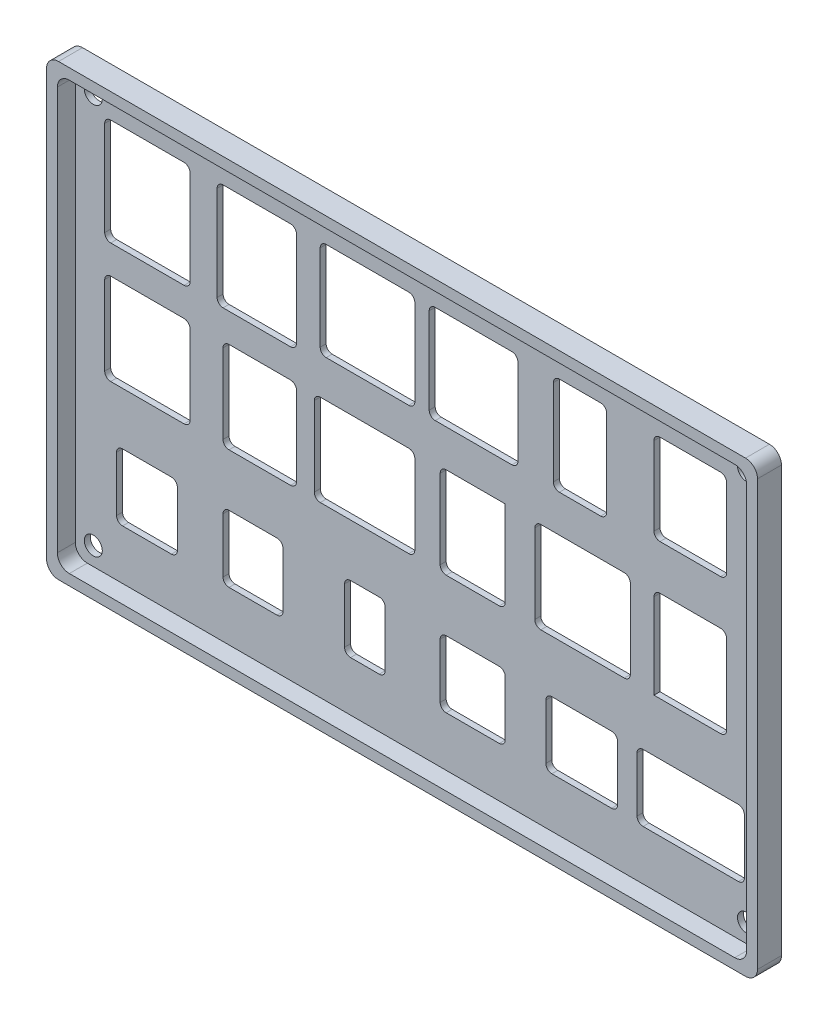
SolidWorks part; units mm, degrees
ref_plane "Front Plane" through (0, 0, 0) normal (0, 0, 1) x (1, 0, 0)
ref_plane "Top Plane" through (0, 0, 0) normal (0, 1, 0) x (1, 0, 0)
ref_plane "Right Plane" through (0, 0, 0) normal (1, 0, 0) x (0, 0, -1)
sketch "Sketch1" plane through (0, 0, 0) normal (0, 0, 1) x (1, 0, 0)
  line L1 (-44.9273, 28.8963) -> (70.105, 28.8963)
  line L2 (-44.9273, 28.8963) -> (-44.9273, -42.4043)
  line L3 (-44.9273, -42.4043) -> (70.105, -42.4043)
  line L4 (70.105, 28.8963) -> (70.105, -42.4043)
  line L5 (-40.0243, 23.5886) -> (-25.7822, 23.5886)
  line L6 (-40.0243, 23.5886) -> (-40.0243, 5.8213)
  line L7 (-40.0243, 5.8213) -> (-25.7822, 5.8213)
  line L8 (-25.7822, 23.5886) -> (-25.7822, 5.8213)
  line L9 (-21.2699, 23.5886) -> (-8.0149, 23.5886)
  line L10 (-21.2699, 23.5886) -> (-21.2699, 5.8213)
  line L11 (-21.2699, 5.8213) -> (-8.0149, 5.8213)
  line L12 (-8.0149, 23.5886) -> (-8.0149, 5.8213)
  line L13 (-4.0666, 23.5886) -> (11.7266, 23.5886)
  line L14 (-4.0666, 23.5886) -> (-4.0666, 7.2314)
  line L15 (-4.0666, 7.2314) -> (11.7266, 7.2314)
  line L16 (11.7266, 23.5886) -> (11.7266, 7.2314)
  line L17 (14.1238, 23.5886) -> (28.9299, 23.5886)
  line L18 (14.1238, 23.5886) -> (14.1238, 7.2314)
  line L19 (14.1238, 7.2314) -> (28.9299, 7.2314)
  line L20 (28.9299, 23.5886) -> (28.9299, 7.2314)
  line L21 (34.8524, 23.5886) -> (43.736, 23.5886)
  line L22 (34.8524, 23.5886) -> (34.8524, 7.2314)
  line L23 (34.8524, 7.2314) -> (43.736, 7.2314)
  line L24 (43.736, 23.5886) -> (43.736, 7.2314)
  line L25 (51.6326, 23.5886) -> (63.7595, 23.5886)
  line L26 (51.6326, 23.5886) -> (51.6326, 8.5005)
  line L27 (51.6326, 8.5005) -> (63.7595, 8.5005)
  line L28 (63.7595, 23.5886) -> (63.7595, 8.5005)
  line L29 (-40.0243, 1.0269) -> (-25.7822, 1.0269)
  line L30 (-40.0243, 1.0269) -> (-40.0243, -14.2022)
  line L31 (-40.0243, -14.2022) -> (-25.7822, -14.2022)
  line L32 (-25.7822, 1.0269) -> (-25.7822, -14.2022)
  line L33 (-20.2828, 1.0269) -> (-8.0149, 1.0269)
  line L34 (-20.2828, 1.0269) -> (-20.2828, -14.2022)
  line L35 (-20.2828, -14.2022) -> (-8.0149, -14.2022)
  line L36 (-8.0149, 1.0269) -> (-8.0149, -14.2022)
  line L37 (-5.0536, 1.0269) -> (11.7266, 1.0269)
  line L38 (-5.0536, 1.0269) -> (-5.0536, -14.2022)
  line L39 (-5.0536, -14.2022) -> (11.7266, -14.2022)
  line L40 (11.7266, 1.0269) -> (11.7266, -14.2022)
  line L41 (15.9569, 1.0269) -> (26.8148, 1.0269)
  line L42 (15.9569, 1.0269) -> (15.9569, -14.2022)
  line L43 (15.9569, -14.2022) -> (26.8148, -14.2022)
  line L44 (26.8148, 1.0269) -> (26.8148, -14.2022)
  line L45 (31.7501, 1.0269) -> (47.6843, 1.0269)
  line L46 (31.7501, 1.0269) -> (31.7501, -14.2022)
  line L47 (31.7501, -14.2022) -> (47.6843, -14.2022)
  line L48 (47.6843, 1.0269) -> (47.6843, -14.2022)
  line L49 (51.6326, 1.0269) -> (63.7595, 1.0269)
  line L50 (51.6326, 1.0269) -> (51.6326, -14.2022)
  line L51 (51.6326, -14.2022) -> (63.7595, -14.2022)
  line L52 (63.7595, 1.0269) -> (63.7595, -14.2022)
  line L53 (-38.0501, -22.9449) -> (-27.8974, -22.9449)
  line L54 (-38.0501, -22.9449) -> (-38.0501, -34.0847)
  line L55 (-38.0501, -34.0847) -> (-27.8974, -34.0847)
  line L56 (-27.8974, -22.9449) -> (-27.8974, -34.0847)
  line L57 (-20.2828, -22.9449) -> (-10.271, -22.9449)
  line L58 (-20.2828, -22.9449) -> (-20.2828, -34.0847)
  line L59 (-20.2828, -34.0847) -> (-10.271, -34.0847)
  line L60 (-10.271, -22.9449) -> (-10.271, -34.0847)
  line L61 (0, -22.9449) -> (6.7912, -22.9449)
  line L62 (0, -22.9449) -> (0, -34.0847)
  line L63 (0, -34.0847) -> (6.7912, -34.0847)
  line L64 (6.7912, -22.9449) -> (6.7912, -34.0847)
  line L65 (15.9569, -22.9449) -> (26.8148, -22.9449)
  line L66 (15.9569, -22.9449) -> (15.9569, -34.0847)
  line L67 (15.9569, -34.0847) -> (26.8148, -34.0847)
  line L68 (26.8148, -22.9449) -> (26.8148, -34.0847)
  line L69 (33.5833, -22.9449) -> (45.5692, -22.9449)
  line L70 (33.5833, -22.9449) -> (33.5833, -34.0847)
  line L71 (33.5833, -34.0847) -> (45.5692, -34.0847)
  line L72 (45.5692, -22.9449) -> (45.5692, -34.0847)
  line L73 (48.8124, -22.9449) -> (66.7207, -22.9449)
  line L74 (48.8124, -22.9449) -> (48.8124, -34.0847)
  line L75 (48.8124, -34.0847) -> (66.7207, -34.0847)
  line L76 (66.7207, -22.9449) -> (66.7207, -34.0847)
  circle A0 centre (-41.9273, 25.8963) radius 1.5
  circle A1 centre (67.0727, 25.8963) radius 1.5
  circle A2 centre (67.0727, -39.3537) radius 1.5
  circle A3 centre (-41.9273, -39.3537) radius 1.5
extrude "Boss-Extrude1" add sketch "Sketch1" along normal blind 1
fillet "Fillet1" radius 2 4 edges at (70.105, 28.8963, 0.5) (70.105, -42.4043, 0.5) (-44.9273, -42.4043, 0.5) (-44.9273, 28.8963, 0.5)
sketch "Sketch2" plane through (0, 0, 0) normal (0, 0, -1) x (-1, 0, 0)
  line L0 (-68.105, 28.8963) -> (42.9273, 28.8963) construction
  line L1 (-70.105, 28.8963) -> (44.9273, 28.8963)
  line L2 (-70.105, 28.8963) -> (-70.105, -42.4043)
  line L3 (-70.105, -42.4043) -> (44.9273, -42.4043)
  line L4 (44.9273, 28.8963) -> (44.9273, -42.4043)
  line L5 (44.9273, 26.8963) -> (44.9273, -40.4043) construction
  line L6 (42.9273, -42.4043) -> (-68.105, -42.4043) construction
  line L7 (-70.105, -40.4043) -> (-70.105, 26.8963) construction
  dimension "D1" = 0
  dimension "D2" = 0
  dimension "D3" = 0
  dimension "D4" = 0
extrude "Extrude-Thin1" add sketch "Sketch2" against normal blind 4 separate body thin thin type one direction wall 1.8
fillet "Fillet2" radius 2 8 edges at (71.905, 30.6963, 2) (71.905, -44.2043, 2) (-46.7273, -44.2043, 2) (-46.7273, 30.6963, 2) (70.105, -42.4043, 2) (70.105, 28.8963, 2) (-44.9273, -42.4043, 2) (-44.9273, 28.8963, 2)
fillet "Fillet6" radius 1 70 edges at (48.8124, -34.0847, 0.5) (-40.0243, -14.2022, 0.5) (-20.2828, -14.2022, 0.5) (-38.0501, -34.0847, 0.5) (-20.2828, -34.0847, 0.5) (-5.0536, -14.2022, 0.5) (0, -34.0847, 0.5) (15.9569, -34.0847, 0.5) (15.9569, -14.2022, 0.5) (31.7501, -14.2022, 0.5) (33.5833, -34.0847, 0.5) (-25.7822, -14.2022, 0.5) (-8.0149, -14.2022, 0.5) (-27.8974, -34.0847, 0.5) (-10.271, -34.0847, 0.5) (11.7266, -14.2022, 0.5) (6.7912, -34.0847, 0.5) (26.8148, -34.0847, 0.5) (26.8148, -14.2022, 0.5) (45.5692, -34.0847, 0.5) (47.6843, -14.2022, 0.5) (66.7207, -34.0847, 0.5) (63.7595, -14.2022, 0.5) (-25.7822, 1.0269, 0.5) (-27.8974, -22.9449, 0.5) (-10.271, -22.9449, 0.5) (-8.0149, 1.0269, 0.5) (11.7266, 1.0269, 0.5) (6.7912, -22.9449, 0.5) (26.8148, -22.9449, 0.5) (47.6843, 1.0269, 0.5) (45.5692, -22.9449, 0.5) (63.7595, 1.0269, 0.5) (66.7207, -22.9449, 0.5) (33.5833, -22.9449, 0.5) (48.8124, -22.9449, 0.5) (51.6326, 1.0269, 0.5) (31.7501, 1.0269, 0.5) (15.9569, 1.0269, 0.5) (15.9569, -22.9449, 0.5) (0, -22.9449, 0.5) (-5.0536, 1.0269, 0.5) (-20.2828, 1.0269, 0.5) (-20.2828, -22.9449, 0.5) (-38.0501, -22.9449, 0.5) (-40.0243, 1.0269, 0.5) (51.6326, 8.5005, 0.5) (63.7595, 8.5005, 0.5) (51.6326, 23.5886, 0.5) (63.7595, 23.5886, 0.5) (43.736, 23.5886, 0.5) (34.8524, 23.5886, 0.5) (34.8524, 7.2314, 0.5) (43.736, 7.2314, 0.5) (14.1238, 7.2314, 0.5) (28.9299, 7.2314, 0.5) (14.1238, 23.5886, 0.5) (28.9299, 23.5886, 0.5) (-4.0666, 7.2314, 0.5) (-4.0666, 23.5886, 0.5) (11.7266, 7.2314, 0.5) (11.7266, 23.5886, 0.5) (-8.0149, 23.5886, 0.5) (-8.0149, 5.8213, 0.5) (-21.2699, 5.8213, 0.5) (-21.2699, 23.5886, 0.5) (-40.0243, 23.5886, 0.5) (-25.7822, 23.5886, 0.5) (-25.7822, 5.8213, 0.5) (-40.0243, 5.8213, 0.5)
